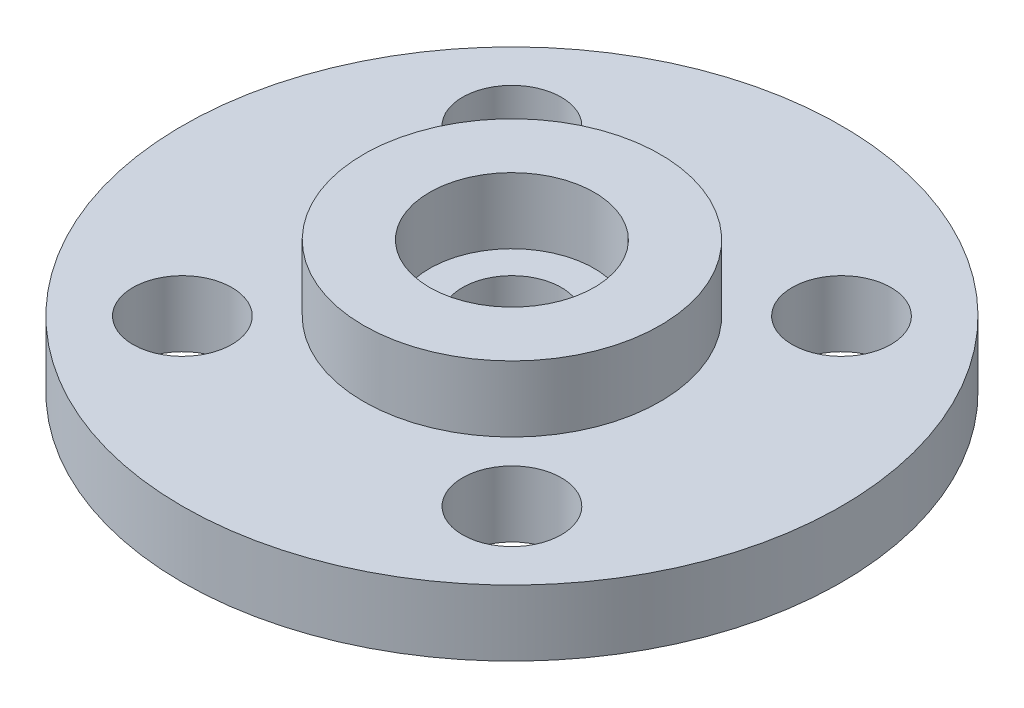
SolidWorks part; units mm, degrees
ref_plane "Front Plane" through (0, 0, 0) normal (0, 0, 1) x (1, 0, 0)
ref_plane "Top Plane" through (0, 0, 0) normal (0, 1, 0) x (1, 0, 0)
ref_plane "Right Plane" through (0, 0, 0) normal (1, 0, 0) x (0, 0, -1)
sketch "Sketch1" plane through (0, 0, 0) normal (0, 1, 0) x (1, 0, 0)
  line L1 (5, -5) -> (-5, -5) construction
  line L2 (5, -5) -> (5, 5) construction
  line L3 (5, 5) -> (-5, 5) construction
  line L4 (-5, -5) -> (-5, 5) construction
  line L5 (5, -5) -> (-5, 5) construction
  line L6 (5, 5) -> (-5, -5) construction
  circle A0 centre (0, 0) radius 10
  circle A1 centre (0, 0) radius 1.5
  circle A2 centre (-5, 5) radius 1.5
  circle A3 centre (5, 5) radius 1.5
  circle A4 centre (5, -5) radius 1.5
  circle A5 centre (-5, -5) radius 1.5
  dimension "D1" = 20
  dimension "D2" = 3
  dimension "D4" = 3
  dimension "D5" = 3
  dimension "D6" = 3
  dimension "D7" = 3
  dimension "D3" = 10
extrude "Boss-Extrude1" add sketch "Sketch1" along normal blind 2
sketch "Sketch2" plane through (0, 2, 0) normal (0, 1, 0) x (1, 0, 0)
  circle A0 centre (0, 0) radius 2.5
  circle A1 centre (0, 0) radius 4.5
  dimension "D1" = 5
  dimension "D2" = 9
extrude "Boss-Extrude2" add sketch "Sketch2" along normal blind 2
